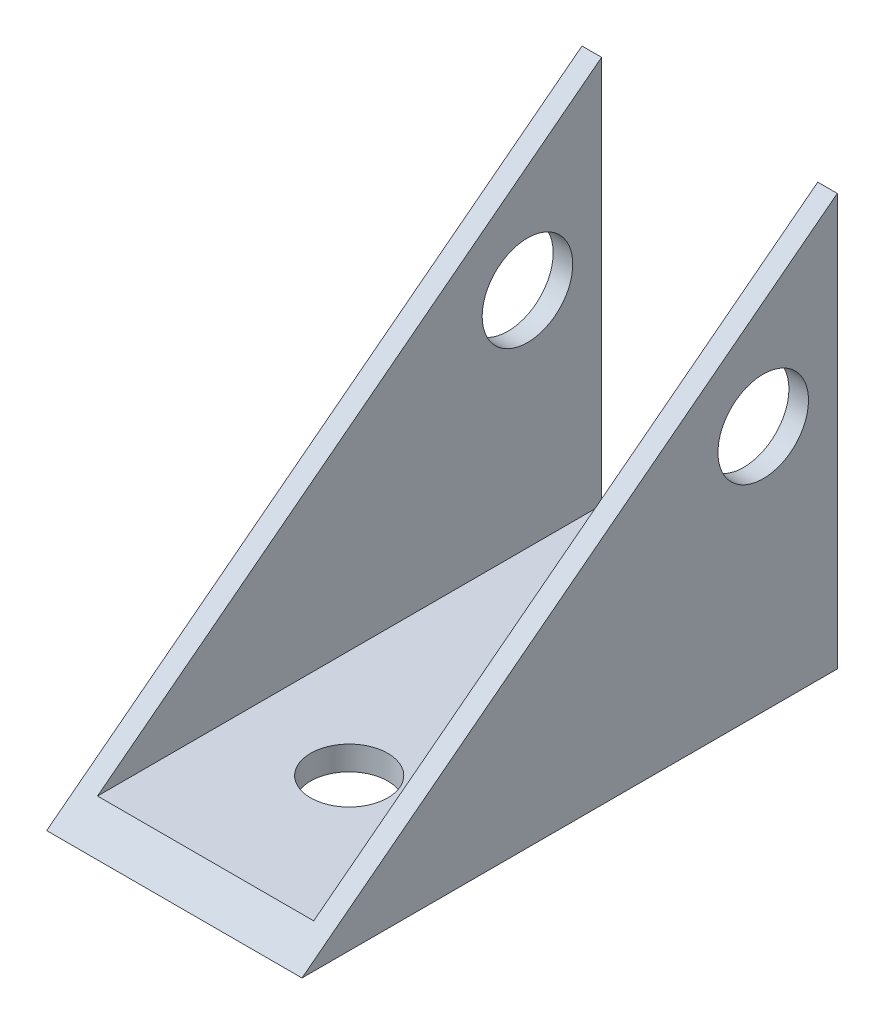
SolidWorks part; units mm, degrees
ref_plane "Front" through (0, 0, 0) normal (0, 0, 1) x (1, 0, 0)
ref_plane "Top" through (0, 0, 0) normal (0, 1, 0) x (1, 0, 0)
ref_plane "Right" through (0, 0, 0) normal (1, 0, 0) x (0, 0, -1)
sketch "Sketch1" plane through (0, 0, 0) normal (1, 0, 0) x (0, 0, -1)
  line L0 (0, 0) -> (65, 0)
  line L1 (65, 0) -> (65, 50)
  line L2 (65, 50) -> (0, 0)
  circle A0 centre (56, 30) radius 5.5
  dimension "D5" = 11
  dimension "D1" = 30
  dimension "D2" = 65
  dimension "D3" = 50
  dimension "D4" = 9
extrude "Boss-Extrude1" add sketch "Sketch1" along normal blind 31
sketch "Sketch2" plane through (0, 0, -65) normal (0, 0, -1) x (-1, 0, 0)
  line L0 (-31, 50) -> (0, 50) construction
  line L1 (-28.6237, 2.9218) -> (-28.6237, 55.1392)
  line L2 (-28.6237, 2.9218) -> (-2.3763, 2.9218)
  line L3 (-28.6237, 55.1392) -> (-2.3763, 55.1392)
  line L4 (-2.3763, 2.9218) -> (-2.3763, 55.1392)
  line L5 (-28.6237, 2.9218) -> (-2.3763, 55.1392) construction
  line L6 (-28.6237, 55.1392) -> (-2.3763, 2.9218) construction
  line L7 (-15.5, 50) -> (-15.5, 19.4596) construction
  point P4 (-15.5, 24.956)
  point P5 (-15.5, 29.0305)
  point P12 (0, 0)
extrude "Cut-Extrude1" cut sketch "Sketch2" against normal through all
sketch "Sketch5" plane through (0, 2.9218, 0) normal (0, 1, 0) x (1, 0, 0)
  line L0 (0, 65) -> (31, 65) construction
  line L1 (15.5, 76.6493) -> (15.5, 60.9334) construction
  line L2 (18.6018, 76.6493) -> (18.6018, 60.9334)
  line L3 (12.3982, 76.6493) -> (12.3982, 60.9334)
  arc A0 (18.6018, 76.6493) -> (12.3982, 76.6493) centre (15.5, 76.6493) ccw
  arc A1 (12.3982, 60.9334) -> (18.6018, 60.9334) centre (15.5, 60.9334) ccw
  circle A2 centre (15.5, 21.23) radius 4.6882
  point P6 (15.5, 68.7914)
extrude "Cut-Extrude2" cut sketch "Sketch5" against normal through all
